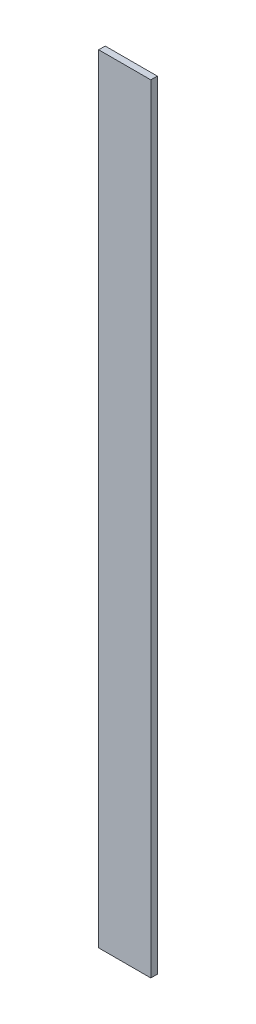
SolidWorks part; units mm, degrees
ref_plane "Front Plane" through (0, 0, 0) normal (0, 0, 1) x (1, 0, 0)
ref_plane "Top Plane" through (0, 0, 0) normal (0, 1, 0) x (1, 0, 0)
ref_plane "Right Plane" through (0, 0, 0) normal (1, 0, 0) x (0, 0, -1)
other "Configuration Table"
sketch "Sketch1" plane through (0, 0, 0) normal (0, 0, 1) x (1, 0, 0)
  line L1 (702, 1469) -> (714, 1469)
  line L2 (702, 1469) -> (702, 1648)
  line L3 (702, 1648) -> (714, 1648)
  line L4 (714, 1469) -> (714, 1648)
extrude "DET2_on_sove_dilimi_1" add sketch "Sketch1" along normal blind 1.5 from offset 38.5 separate body
